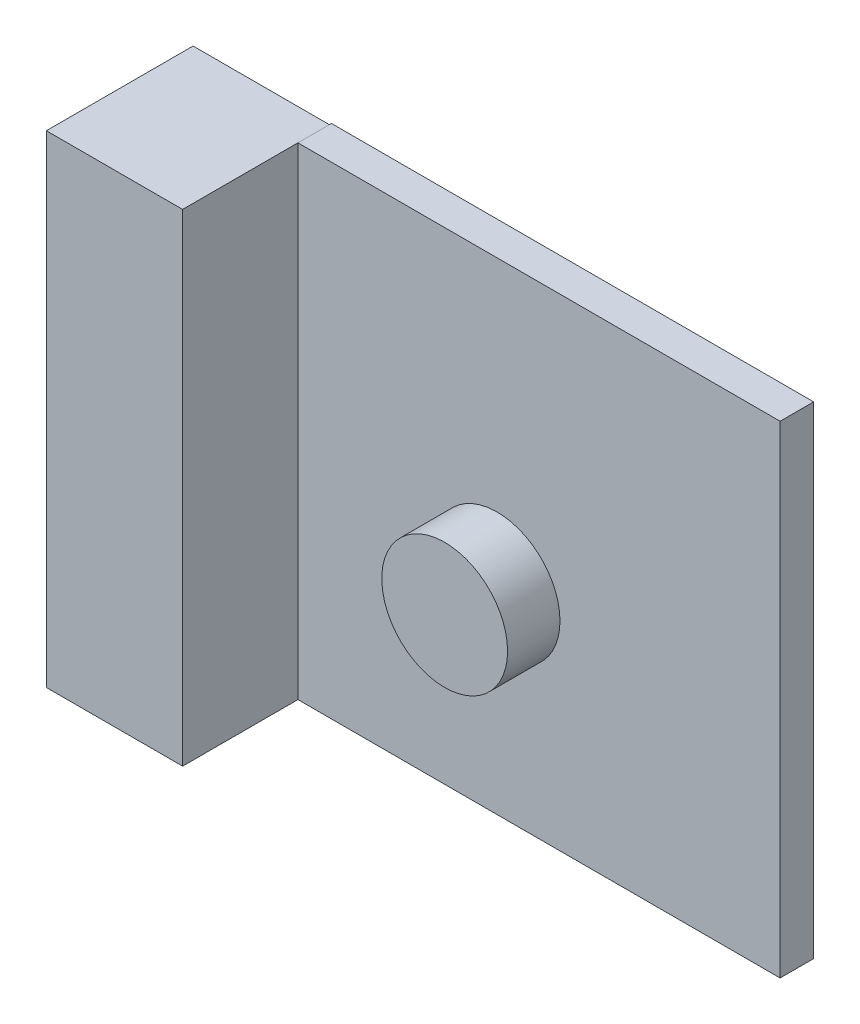
SolidWorks part; units mm, degrees
ref_plane "Front Plane" through (0, 0, 0) normal (0, 0, 1) x (1, 0, 0)
ref_plane "Top Plane" through (0, 0, 0) normal (0, 1, 0) x (1, 0, 0)
ref_plane "Right Plane" through (0, 0, 0) normal (1, 0, 0) x (0, 0, -1)
other "Configuration Table"
sketch "Sketch1" plane through (0, 0, 0) normal (0, 0, 1) x (1, 0, 0)
  circle A0 centre (58, 130) radius 3
extrude "magnet" add sketch "Sketch1" along normal blind 2.5 from offset 35.5 separate body
sketch "Sketch2" plane through (0, 0, 0) normal (1, 0, 0) x (0, 0, -1)
  line L1 (39.1, 118.5) -> (37.5, 118.5)
  line L2 (39.1, 118.5) -> (39.1, 141.5)
  line L3 (39.1, 141.5) -> (37.5, 141.5)
  line L4 (37.5, 118.5) -> (37.5, 141.5)
  line L5 (39.1, 118.5) -> (37.5, 141.5) construction
  line L6 (39.1, 141.5) -> (37.5, 118.5) construction
extrude "as5600_board" add sketch "Sketch2" along normal blind 23 from offset 46.5 separate body
sketch "Sketch3" plane through (0, 0, 0) normal (1, 0, 0) x (0, 0, -1)
  line L1 (39, 118.5) -> (32, 118.5)
  line L2 (39, 118.5) -> (39, 141.5)
  line L3 (39, 141.5) -> (32, 141.5)
  line L4 (32, 118.5) -> (32, 141.5)
  line L5 (39, 118.5) -> (32, 141.5) construction
  line L6 (39, 141.5) -> (32, 118.5) construction
extrude "sensor_bracket" add sketch "Sketch3" along normal blind 6.5 from offset 40 separate body
